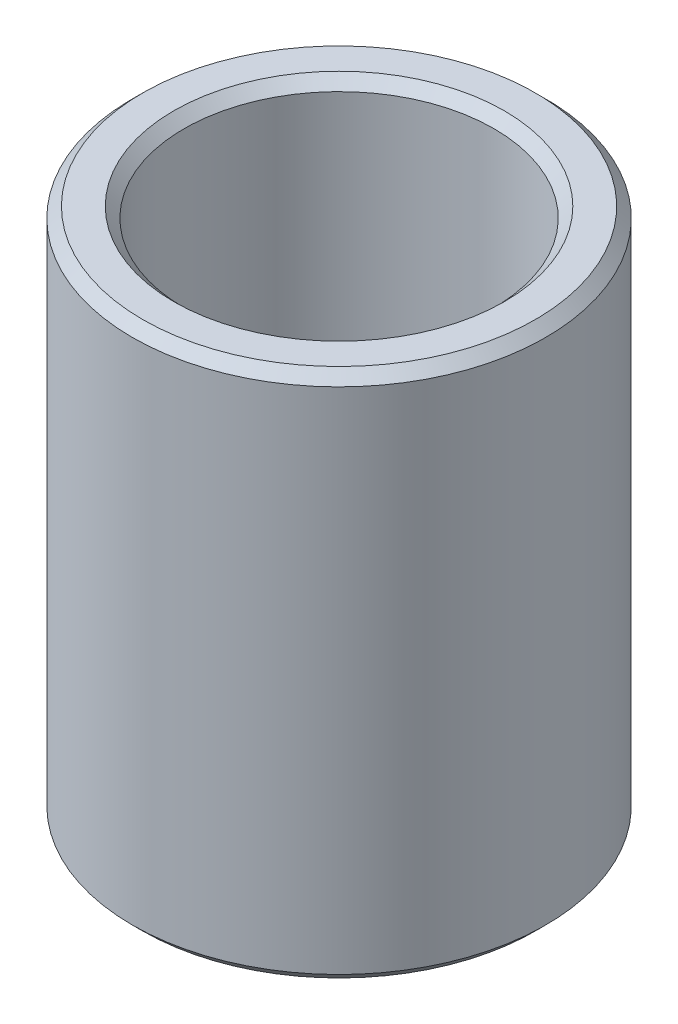
SolidWorks part; units mm, degrees
ref_plane "Front" through (0, 0, 0) normal (0, 0, 1) x (1, 0, 0)
ref_plane "Top" through (0, 0, 0) normal (0, 1, 0) x (1, 0, 0)
ref_plane "Right" through (0, 0, 0) normal (1, 0, 0) x (0, 0, -1)
sketch "Skizze1" plane through (0, 0, 0) normal (0, 1, 0) x (1, 0, 0)
  circle A0 centre (0, 0) radius 4
  circle A1 centre (0, 0) radius 3
  dimension "D1" = 8
  dimension "D2" = 6
extrude "Aufsatz-Linear austragen1" add sketch "Skizze1" along normal blind 10.25
chamfer "Fase1" distance 0.2 angle 45 4 edges at (0, 0, 4) (0, 10.25, 4) (0, 0, 3) (0, 10.25, 3)
